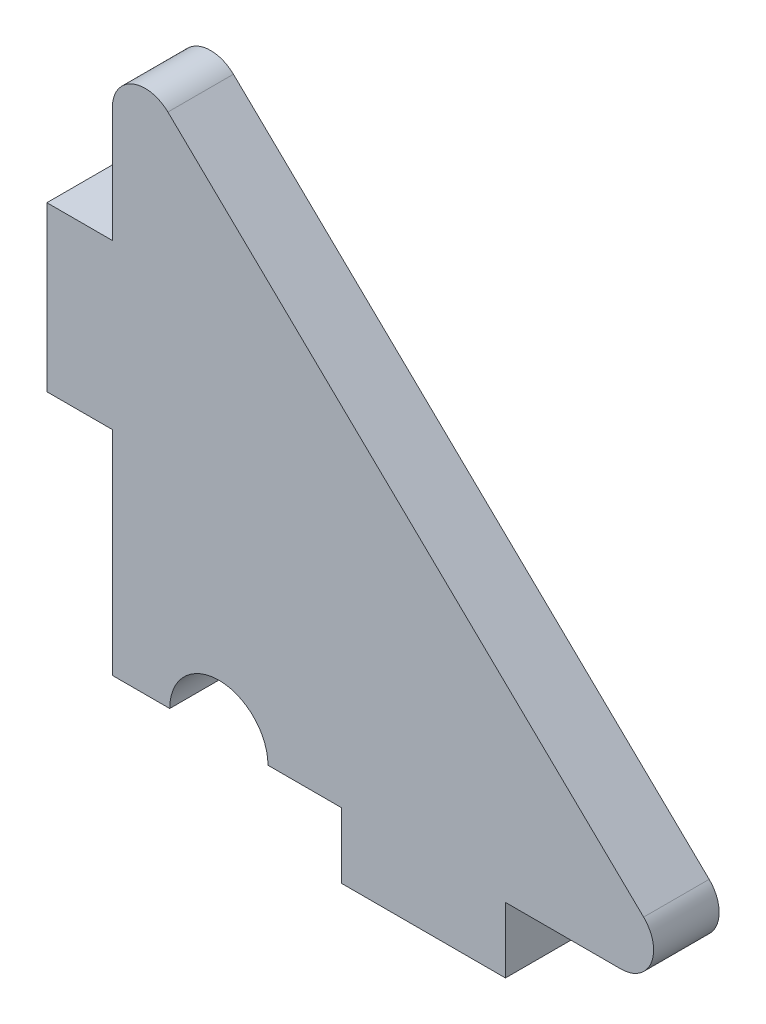
SolidWorks part; units mm, degrees
ref_plane "Front Plane" through (0, 0, 0) normal (0, 0, 1) x (1, 0, 0)
ref_plane "Top Plane" through (0, 0, 0) normal (0, 1, 0) x (1, 0, 0)
ref_plane "Right Plane" through (0, 0, 0) normal (1, 0, 0) x (0, 0, -1)
sketch "Sketch1" plane through (0, 0, 0) normal (0, 0, 1) x (1, 0, 0)
  line L0 (0, 0) -> (3.5, 0)
  line L1 (14, 0) -> (14, -4)
  line L2 (14, -4) -> (24, -4)
  line L3 (24, -4) -> (24, 0)
  line L4 (24, 0) -> (31.0494, 0)
  line L5 (0, 0) -> (0, 13)
  line L6 (0, 13) -> (-4, 13)
  line L7 (-4, 13) -> (-4, 23)
  line L8 (-4, 23) -> (0, 23)
  line L9 (0, 23) -> (0, 30.0494)
  line L10 (3.3892, 31.4882) -> (32.4386, 3.4388)
  line L11 (14, 0) -> (9.5, 0)
  arc A0 (32.4386, 3.4388) -> (31.0494, 0) centre (31.0494, 2) cw
  arc A1 (3.3892, 31.4882) -> (0, 30.0494) centre (2, 30.0494) ccw
  arc A2 (9.5, 0) -> (3.5, 0) centre (6.5, 0) ccw
  point P13 (36, 0)
  dimension "D6" = 2
  dimension "D7" = 6
  dimension "D1" = 14
  dimension "D2" = 4
  dimension "D3" = 10
  dimension "D4" = 12
  dimension "D5" = 13
  dimension "D8" = 6.5
extrude "Boss-Extrude1" add sketch "Sketch1" along normal blind 4
